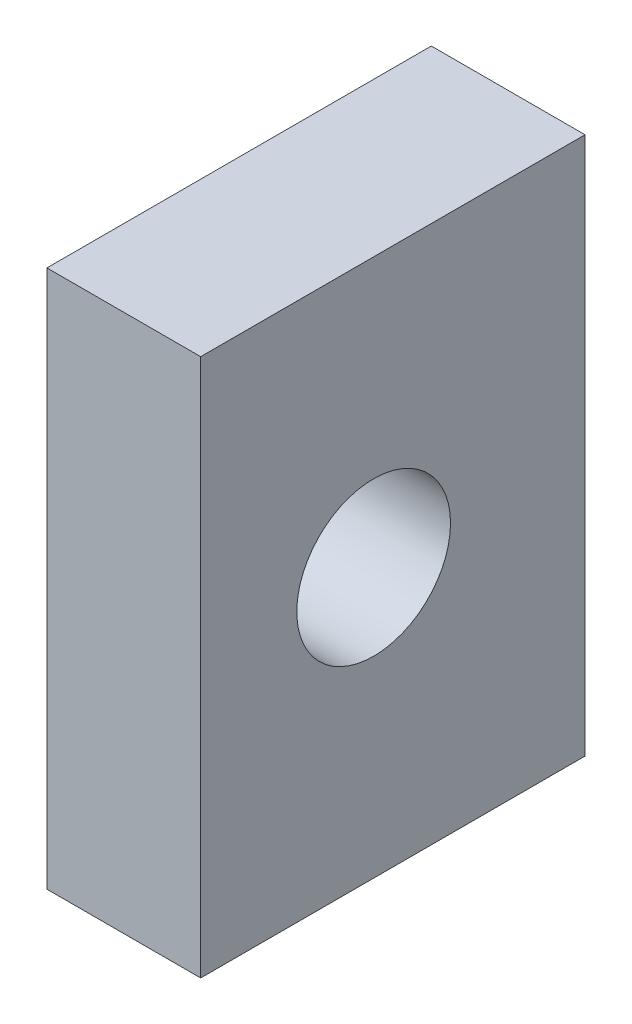
SolidWorks part; units mm, degrees
ref_plane "Front Plane" through (0, 0, 0) normal (0, 0, 1) x (1, 0, 0)
ref_plane "Top Plane" through (0, 0, 0) normal (0, 1, 0) x (1, 0, 0)
ref_plane "Right Plane" through (0, 0, 0) normal (1, 0, 0) x (0, 0, -1)
sketch "Sketch1" plane through (0, 0, 0) normal (1, 0, 0) x (0, 0, -1)
  line L1 (-15.875, -22.225) -> (15.875, -22.225)
  line L2 (-15.875, -22.225) -> (-15.875, 22.225)
  line L3 (-15.875, 22.225) -> (15.875, 22.225)
  line L4 (15.875, -22.225) -> (15.875, 22.225)
  line L5 (-15.875, -22.225) -> (15.875, 22.225) construction
  line L6 (-15.875, 22.225) -> (15.875, -22.225) construction
  circle A0 centre (-1.5875, 0) radius 6.35
  point P0 (0, 0)
  dimension "D3" = 12.7
  dimension "D4" = 14.2875
  dimension "D1" = 44.45
  dimension "D2" = 31.75
extrude "Boss-Extrude1" add sketch "Sketch1" along normal blind 12.7
